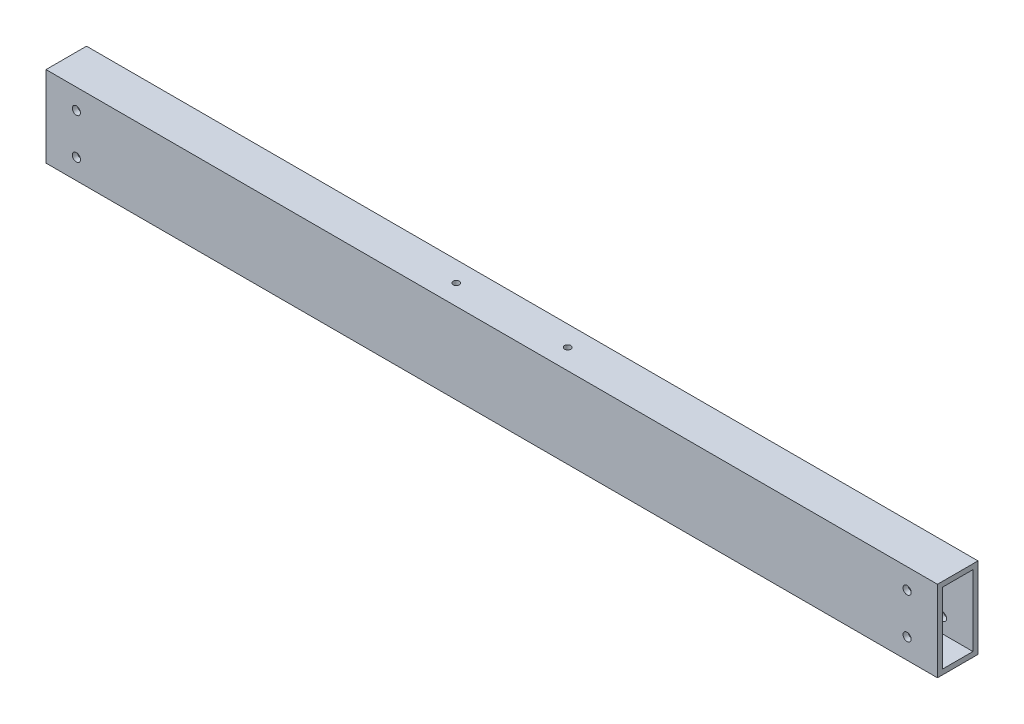
SolidWorks part; units mm, degrees
material "6061-T6 (SS)"
ref_plane "Front Plane" through (0, 0, 0) normal (0, 0, 1) x (1, 0, 0)
ref_plane "Top Plane" through (0, 0, 0) normal (0, 1, 0) x (1, 0, 0)
ref_plane "Right Plane" through (0, 0, 0) normal (1, 0, 0) x (0, 0, -1)
sketch "Sketch1" plane through (0, 0, 0) normal (0, 0, 1) x (1, 0, 0)
  line L1 (-279.4, 25.4) -> (279.4, 25.4)
  line L2 (-279.4, 25.4) -> (-279.4, -25.4)
  line L3 (-279.4, -25.4) -> (279.4, -25.4)
  line L4 (279.4, 25.4) -> (279.4, -25.4)
  line L5 (-279.4, 25.4) -> (279.4, -25.4) construction
  line L6 (-279.4, -25.4) -> (279.4, 25.4) construction
  point P0 (0, 0)
  dimension "D1" = 50.8
  dimension "D2" = 558.8
extrude "Boss-Extrude1" add sketch "Sketch1" along normal mid plane 25.4
sketch "Sketch2" plane through (279.4, 0, 0) normal (1, 0, 0) x (0, 0, -1)
  line L8 (9.525, -22.225) -> (9.525, 22.225)
  line L9 (9.525, 22.225) -> (-9.525, 22.225)
  line L10 (-9.525, 22.225) -> (-9.525, -22.225)
  line L11 (-9.525, -22.225) -> (9.525, -22.225)
  line L12 (9.525, -22.225) -> (9.525, 22.225)
  line L13 (9.525, 22.225) -> (-9.525, 22.225)
  line L14 (-9.525, 22.225) -> (-9.525, -22.225)
  line L15 (-9.525, -22.225) -> (9.525, -22.225)
  dimension "D1" = 3.175
extrude "Cut-Extrude1" cut sketch "Sketch2" against normal through all
sketch "Sketch3" plane through (0, 0, 12.7) normal (0, 0, 1) x (1, 0, 0)
sketch "Sketch4" plane through (0, 25.4, 0) normal (0, 1, 0) x (1, 0, 0)
  line L0 (-279.4, -12.7) -> (-279.4, 12.7) construction
  line L1 (0, -12.7) -> (0, 12.7) construction
  line L2 (279.4, -12.7) -> (-279.4, -12.7) construction
  line L3 (279.4, 12.7) -> (-279.4, 12.7) construction
  circle A0 centre (-304.8, 0) radius 1.7272
  circle A1 centre (-292.1, 0) radius 1.7272
  circle A3 centre (-266.7, 0) radius 1.7272
  circle A4 centre (-254, 0) radius 1.7272
  circle A5 centre (-241.3, 0) radius 1.7272
  circle A7 centre (241.3, 0) radius 1.7272
  circle A8 centre (254, 0) radius 1.7272
  circle A9 centre (266.7, 0) radius 1.7272
  circle A12 centre (-279.4, 0) radius 1.7272 [skipped]
  circle A14 centre (-228.6, 0) radius 1.7272 [skipped]
  dimension "D2" = 3.4544
  dimension "D3" = 7
  dimension "D4" = 12.7
extrude "Cut-Extrude2" [suppressed] cut sketch "Sketch4" against normal blind 6.35
hole_wizard "1/4-20 Tapped Hole1" positions "Sketch8" profile "Sketch7" tap size "1/4-20" standard "ANSI Inch" end condition through all
sketch "Sketch8" plane through (0, 0, 12.7) normal (0, 0, 1) x (1, 0, 0)
  line L0 (-279.4, 25.4) -> (-279.4, -25.4) construction
  line L1 (279.4, -25.4) -> (279.4, 25.4) construction
  line L2 (-279.4, -25.4) -> (279.4, -25.4) construction
  point P0 (-260.35, 12.7)
  point P2 (-260.35, -12.7)
  point P4 (260.35, 12.7)
  point P6 (260.35, -12.7)
  dimension "D1" = 25.4
  dimension "D2" = 19.05
  dimension "D3" = 25.4
  dimension "D4" = 19.05
  dimension "D5" = 12.7
  dimension "D6" = 12.7
sketch "Sketch7" plane through (-260.35, 12.7, 12.7) normal (1, 0, 0) x (0, -1, 0)
  line L0 (0, 0) -> (0, 25.4)
  line L1 (0, 25.4) -> (2.5527, 25.4)
  line L2 (2.5527, 25.4) -> (2.5527, 0)
  line L5 (2.5527, 0) -> (0, 0)
  line L11 (0, -6.35) -> (0, 107.95) construction
  dimension "Thread Major Dia." = 5.1054
  dimension "Thru Tap Drill Depth" = 25.4
hole_wizard "#10-32 Tapped Hole1" positions "Sketch10" profile "Sketch9" tap size "#10-32" standard "ANSI Inch"
sketch "Sketch10" plane through (0, 0, -12.7) normal (0, 0, -1) x (-1, 0, 0)
  line L0 (-279.4, 25.4) -> (279.4, 25.4) construction
  line L1 (-279.4, -25.4) -> (-279.4, 25.4) construction
  point P0 (-190.5, -13.4937)
  point P15 (-114.3, -13.4937)
  point P16 (-38.1, -13.4937)
  point P17 (38.1, -13.4937)
  point P18 (114.3, -13.4937)
  point P19 (190.5, -13.4937)
  dimension "D1" = 76.2
  dimension "D2" = 38.8937
  dimension "D3" = 88.9
  dimension "D5" = 6
sketch "Sketch9" plane through (190.5, -13.4937, -12.7) normal (1, 0, 0) x (0, 1, 0)
  line L0 (0, 0) -> (0, 6.2933)
  line L1 (0, 6.2933) -> (2.0193, 5.08)
  line L2 (2.0193, 5.08) -> (2.0193, 0)
  line L5 (2.0193, 0) -> (0, 0)
  line L10 (0, 6.2933) -> (-2.0193, 5.08) construction
  line L11 (0, -6.35) -> (0, 107.95) construction
  dimension "Tap Drill Dia." = 4.0386
  dimension "Tap Drill Depth" = 5.08
  dimension "Drill Angle" = 118
hole_wizard "5/32 (0.15625) Diameter Hole1" positions "Sketch12" profile "Sketch11" hole size "5/32" standard "ANSI Inch"
sketch "Sketch12" plane through (0, 25.4, 0) normal (0, 1, 0) x (1, 0, 0)
  line L2 (-34.925, 0) -> (34.925, 0) construction
  point P0 (-34.925, 0)
  point P2 (34.925, 0)
  dimension "D1" = 69.85
sketch "Sketch11" plane through (-34.925, 25.4, 0) normal (1, 0, 0) x (0, 0, 1)
  line L0 (0, 0) -> (0, 6.2723)
  line L1 (0, 6.2723) -> (1.9844, 5.08)
  line L2 (1.9844, 5.08) -> (1.9844, 0)
  line L5 (1.9844, 0) -> (0, 0)
  line L10 (0, 6.2723) -> (-1.9844, 5.08) construction
  line L11 (0, -6.35) -> (0, 107.95) construction
  dimension "Hole Dia." = 3.9688
  dimension "Hole Depth" = 5.08
  dimension "Drill Angle" = 118
